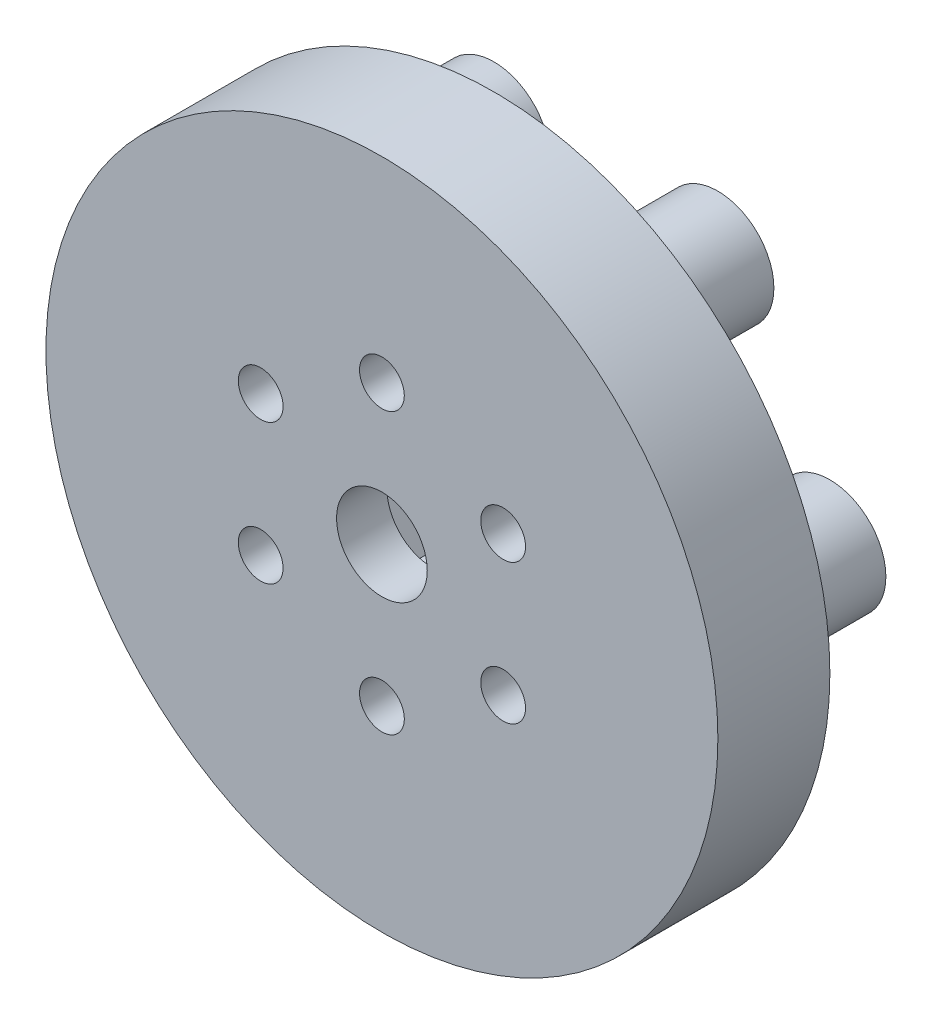
SolidWorks part; units mm, degrees
ref_plane "Front Plane" through (0, 0, 0) normal (0, 0, 1) x (1, 0, 0)
ref_plane "Top Plane" through (0, 0, 0) normal (0, 1, 0) x (1, 0, 0)
ref_plane "Right Plane" through (0, 0, 0) normal (1, 0, 0) x (0, 0, -1)
sketch "Sketch1" plane through (0, 0, 0) normal (0, 0, 1) x (1, 0, 0)
  circle A0 centre (0, 0) radius 20 construction
  circle A1 centre (20, 0) radius 5
  circle A2 centre (10, -17.3205) radius 5
  circle A3 centre (-10, -17.3205) radius 5
  circle A4 centre (-20, 0) radius 5
  circle A5 centre (-10, 17.3205) radius 5
  circle A6 centre (10, 17.3205) radius 5
  point P17 (0, 0)
  dimension "D1" = 40
  dimension "D2" = 10
extrude "Boss-Extrude1" add sketch "Sketch1" along normal blind 10
sketch "Sketch2" plane through (0, 0, 10) normal (0, 0, 1) x (1, 0, 0)
  circle A0 centre (0, 0) radius 30
  circle A1 centre (0, 0) radius 4.05
  circle A2 centre (-0.0006, 12.5) radius 2
  circle A5 centre (10.8255, 6.2513) radius 2
  circle A7 centre (10.8271, -6.2487) radius 2
  circle A9 centre (0.0026, -12.5) radius 2
  circle A11 centre (-10.8235, -6.2513) radius 2
  circle A12 centre (0, 0) radius 12.5 construction
  circle A13 centre (-10.8251, 6.2487) radius 2
  point P6 (0, 0)
  point P7 (0, 0)
  point P29 (0.001, 0)
  dimension "D1" = 60
  dimension "D2" = 4
  dimension "D4" = 8.1
  dimension "D5" = 25
  dimension "D3" = 6
extrude "Boss-Extrude2" add sketch "Sketch2" along normal blind 10
sketch "Sketch5" plane through (0, 0, 10) normal (0, 0, -1) x (-1, 0, 0)
  line L1 (7.621, 0.012) -> (3.8001, 6.606)
  line L2 (3.8001, 6.606) -> (-3.8209, 6.594)
  line L3 (-3.8209, 6.594) -> (-7.621, -0.012)
  line L4 (-7.621, -0.012) -> (-3.8001, -6.606)
  line L5 (-3.8001, -6.606) -> (3.8209, -6.594)
  line L6 (3.8209, -6.594) -> (7.621, 0.012)
  circle A0 centre (0, 0) radius 6.6 construction
  point P1 (4.3987, 7.591)
  dimension "D1" = 13.2
extrude "Cut-Extrude1" cut sketch "Sketch5" against normal blind 5.5
